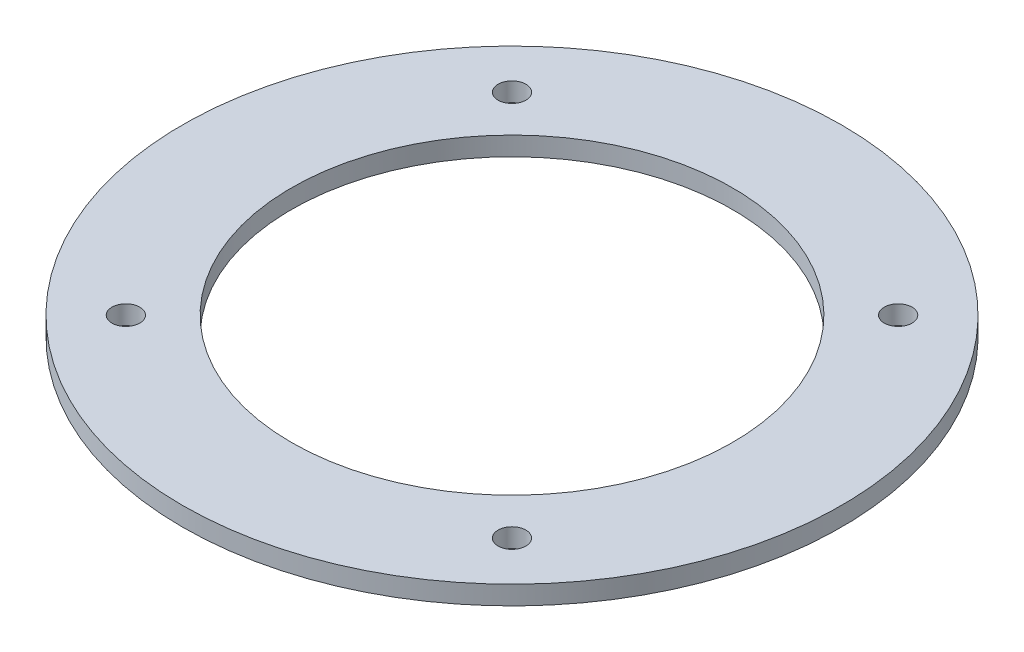
SolidWorks part; units mm, degrees
ref_plane "Front Plane" through (0, 0, 0) normal (0, 0, 1) x (1, 0, 0)
ref_plane "Top Plane" through (0, 0, 0) normal (0, 1, 0) x (1, 0, 0)
ref_plane "Right Plane" through (0, 0, 0) normal (1, 0, 0) x (0, 0, -1)
sketch "Sketch1" plane through (0, 0, 0) normal (0, 1, 0) x (1, 0, 0)
  line L0 (0, 35) -> (0, -35) construction
  line L1 (-35, 0) -> (35, 0) construction
  circle A0 centre (0, 0) radius 23.425
  circle A1 centre (0, 0) radius 35
  circle A2 centre (-20.505, 20.505) radius 1.475
  circle A3 centre (20.505, 20.505) radius 1.475
  circle A4 centre (20.505, -20.505) radius 1.475
  circle A5 centre (-20.505, -20.505) radius 1.475
  dimension "D1" = 46.85
  dimension "D2" = 70
  dimension "D3" = 2.95
  dimension "D4" = 41.01
  dimension "D5" = 41.01
extrude "Boss-Extrude1" add sketch "Sketch1" along normal mid plane 2
